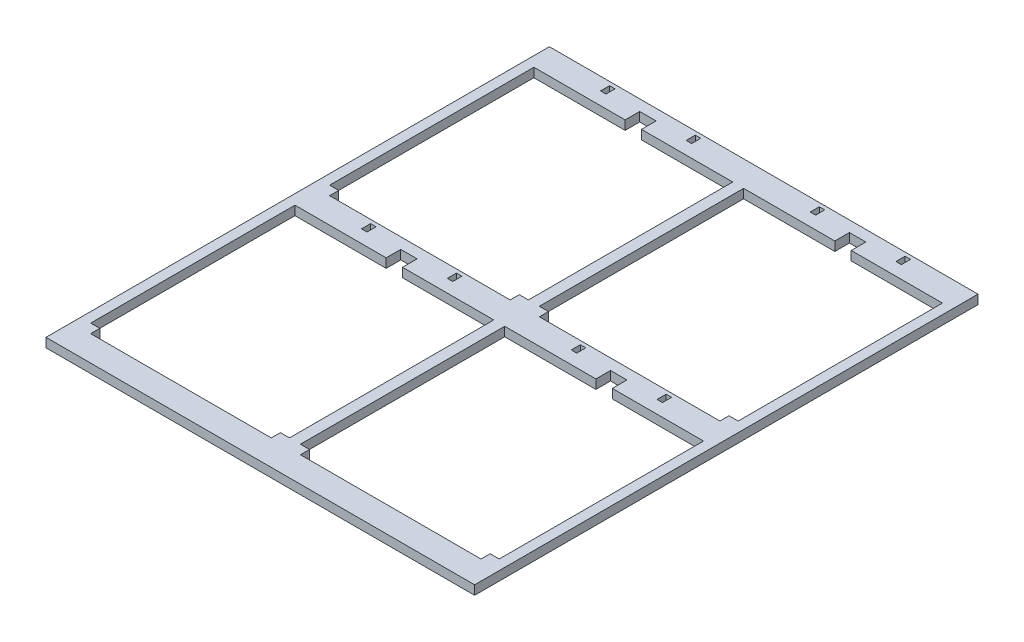
SolidWorks part; units mm, degrees
ref_plane "Front" through (0, 0, 0) normal (0, 0, 1) x (1, 0, 0)
ref_plane "Top" through (0, 0, 0) normal (0, 1, 0) x (1, 0, 0)
ref_plane "Right" through (0, 0, 0) normal (1, 0, 0) x (0, 0, -1)
sketch "Sketch1" plane through (0, 0, 0) normal (0, 1, 0) x (1, 0, 0)
  line L1 (-54.5, 58.5) -> (54.5, 58.5)
  line L2 (-54.5, 58.5) -> (-54.5, -58.5)
  line L3 (-54.5, -58.5) -> (54.5, -58.5)
  line L4 (54.5, 58.5) -> (54.5, -58.5)
  line L5 (-54.5, 58.5) -> (54.5, -58.5) construction
  line L6 (-54.5, -58.5) -> (54.5, 58.5) construction
  line L7 (-60, 72.5) -> (60, 72.5)
  line L8 (-60, 72.5) -> (-60, -72.5)
  line L9 (-60, -72.5) -> (60, -72.5)
  line L10 (60, 72.5) -> (60, -72.5)
  line L11 (-60, 72.5) -> (60, -72.5) construction
  line L12 (-60, -72.5) -> (60, 72.5) construction
  point P0 (0, 0)
  point P6 (0, 0)
  dimension "D1" = 109
  dimension "D2" = 117
  dimension "D3" = 120
  dimension "D4" = 145
extrude "Boss-Extrude1" add sketch "Sketch1" along normal blind 5
sketch "Sketch2" plane through (0, 5, 0) normal (0, 1, 0) x (1, 0, 0)
  line L0 (0, 58.5) -> (-4.5, 58.5)
  line L1 (54.5, 58.5) -> (-54.5, 58.5) construction
  line L2 (0, 58.5) -> (4.5, 58.5)
  line L3 (-4.5, 58.5) -> (-4.5, 66.5)
  line L4 (-4.5, 66.5) -> (4.5, 66.5)
  line L5 (4.5, 66.5) -> (4.5, 58.5)
  line L6 (-4.5, 58.5) -> (4.5, 58.5)
  line M8 (-54.5, 58.5) -> (54.5, 58.5)
  dimension "D1" = 4.5
  dimension "D2" = 4.5
  dimension "D3" = 8
extrude "Cut-Extrude1" cut sketch "Sketch2" against normal blind 10 contours L5 L4 L3 M8
sketch "Sketch5" plane through (0, 5, 0) normal (0, 1, 0) x (1, 0, 0)
  line L0 (-4.5, 58.5) -> (-54.5, 58.5) construction
  line L2 (-25, 70.5) -> (-22, 70.5)
  line L3 (-25, 70.5) -> (-25, 65.5)
  line L4 (-25, 65.5) -> (-22, 65.5)
  line L5 (-22, 70.5) -> (-22, 65.5)
  line L6 (-25, 70.5) -> (-22, 65.5) construction
  line L7 (-25, 65.5) -> (-22, 70.5) construction
  line L9 (-4.5, 58.5) -> (-4.5, 66.5) construction
  point P0 (-23.5, 68)
  dimension "D1" = 5
  dimension "D2" = 3
  dimension "D3" = 7
  dimension "D4" = 20.5
extrude "Cut-Extrude4" cut sketch "Sketch5" against normal through all
mirror "Mirror1" about plane through (0, 0, 0) normal (1, 0, 0) of "Cut-Extrude4"
sketch "Sketch6" plane through (0, 5, 0) normal (0, 1, 0) x (1, 0, 0)
  line L0 (54.5, -58.5) -> (49.5, -58.5)
  line L1 (-54.5, -58.5) -> (54.5, -58.5) construction
  line L2 (49.5, -58.5) -> (49.5, -53.5)
  line L3 (49.5, -53.5) -> (54.5, -53.5)
  line L4 (54.5, -58.5) -> (54.5, 58.5) construction
  line L5 (54.5, -53.5) -> (54.5, -58.5)
  dimension "D1" = 5
  dimension "D2" = 5
extrude "Boss-Extrude2" add sketch "Sketch6" against normal up to vertex (5 mm away)
mirror "Mirror2" about plane through (0, 0, 0) normal (1, 0, 0) of "Boss-Extrude2"
pattern_linear "LPattern1" count 2 spacing 115 along (1, 0, 0) count 2 spacing 131 along (0, 0, 1) of "Boss-Extrude1", "Cut-Extrude4", "Boss-Extrude2", "Mirror1", "Mirror2", "Cut-Extrude1"
